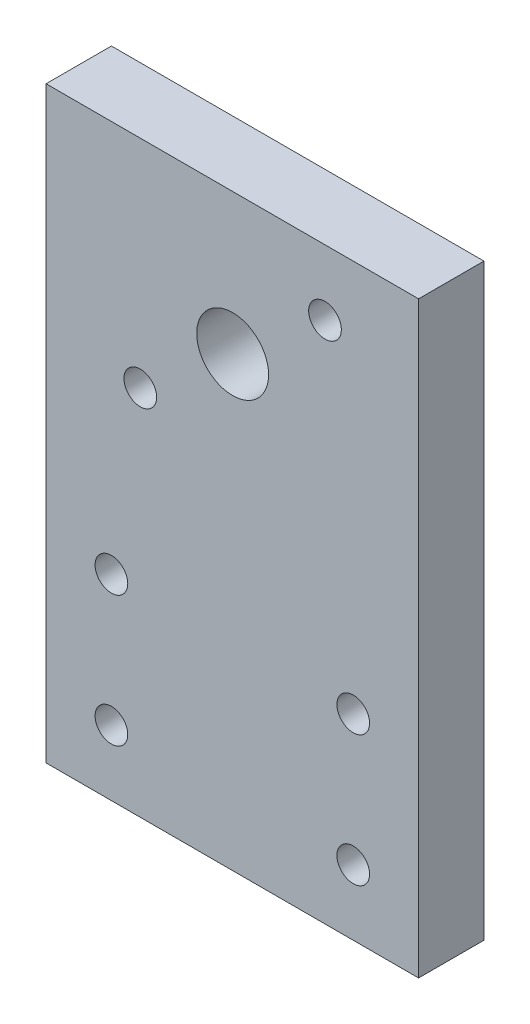
SolidWorks part; units mm, degrees
ref_plane "Front Plane" through (0, 0, 0) normal (0, 0, 1) x (1, 0, 0)
ref_plane "Top Plane" through (0, 0, 0) normal (0, 1, 0) x (1, 0, 0)
ref_plane "Right Plane" through (0, 0, 0) normal (1, 0, 0) x (0, 0, -1)
sketch "Sketch1" plane through (0, 0, 0) normal (0, 0, 1) x (1, 0, 0)
  line L0 (0, 0) -> (57, 0)
  line L1 (57, 0) -> (57, 90)
  line L2 (57, 90) -> (0, 90)
  line L3 (0, 90) -> (0, 0)
  dimension "D1" = 57
  dimension "D2" = 90
extrude "Boss-Extrude1" add sketch "Sketch1" along normal blind 10
sketch "Sketch2" plane through (0, 0, 10) normal (0, 0, 1) x (1, 0, 0)
  line L0 (57, 0) -> (57, 90) construction
  line L1 (0, 0) -> (57, 0) construction
  line L2 (57, 90) -> (0, 90) construction
  line L3 (0, 90) -> (0, 0) construction
  line L4 (42.6801, 80) -> (28.55, 68.45) construction
  line L5 (28.55, 68.45) -> (6.7199, 50.606) construction
  circle A0 centre (47, 30) radius 2.5
  circle A1 centre (47, 10) radius 2.5
  circle A2 centre (10, 10) radius 2.5
  circle A3 centre (10, 30) radius 2.5
  circle A4 centre (28.55, 68.45) radius 5.5
  circle A5 centre (14.4199, 56.9) radius 2.5
  circle A6 centre (42.6801, 80) radius 2.5
  point P22 (0, 0)
  point P24 (44.2271, 82.6032)
  point P25 (43.1226, 79.4364)
  dimension "D1" = 5
  dimension "D6" = 11
  dimension "D11" = 5
  dimension "D2" = 10
  dimension "D3" = 37
  dimension "D4" = 20
  dimension "D5" = 10
  dimension "D7" = 21.55
  dimension "D8" = 28.55
  dimension "D9" = 18.25
  dimension "D10" = 18.25
  dimension "D12" = 10
extrude "Cut-Extrude1" cut sketch "Sketch2" against normal blind 10
